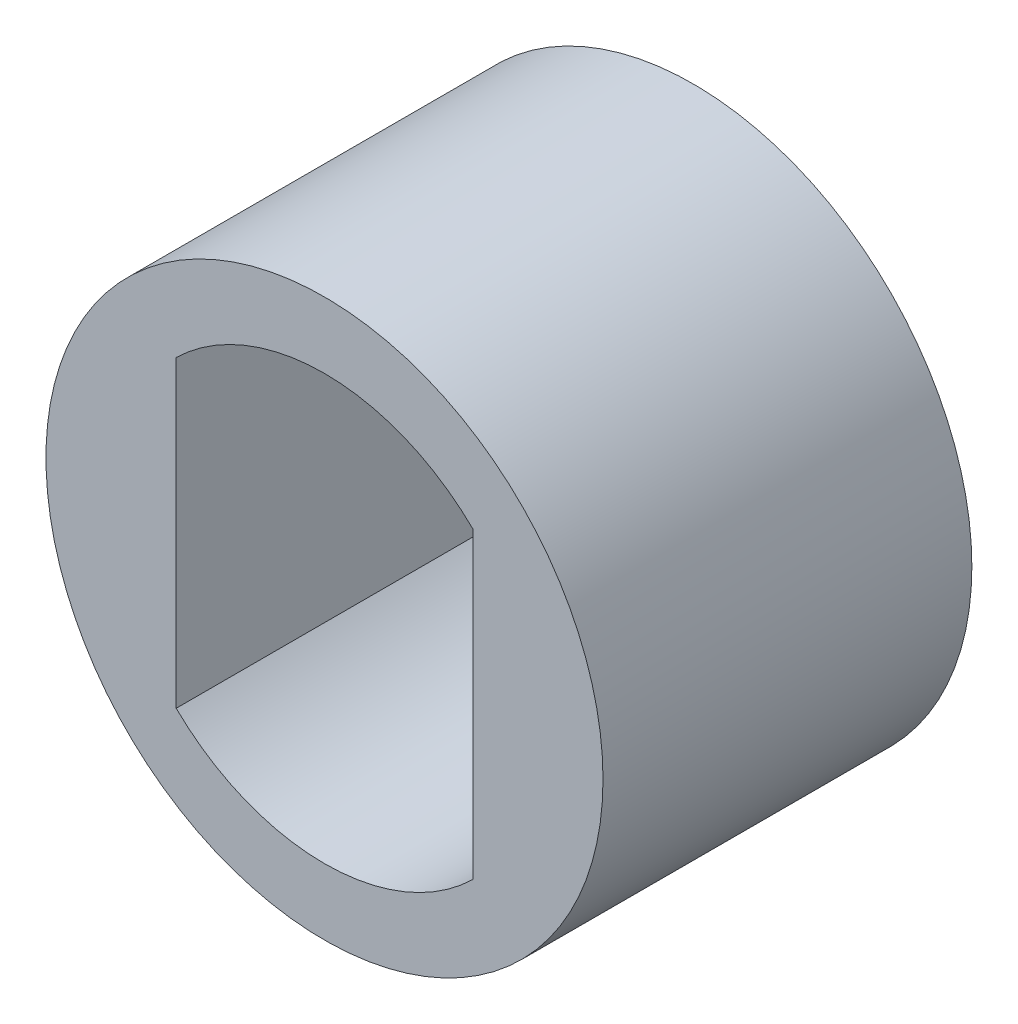
SolidWorks part; units mm, degrees
ref_plane "Plano frontal" through (0, 0, 0) normal (0, 0, 1) x (1, 0, 0)
ref_plane "Plano superior" through (0, 0, 0) normal (0, 1, 0) x (1, 0, 0)
ref_plane "Plano direito" through (0, 0, 0) normal (1, 0, 0) x (0, 0, -1)
sketch "Esboço1" plane through (0, 0, 0) normal (0, 0, 1) x (1, 0, 0)
  line L0 (2.85, -2.3596) -> (2.85, 2.3596) construction
  line L1 (-2.85, 2.3596) -> (-2.85, -2.3596) construction
  line L2 (1.85, -1.9666) -> (1.85, 1.9666) construction
  line L3 (-1.85, 1.9666) -> (-1.85, -1.9666) construction
  arc A0 (-2.85, -2.3596) -> (2.85, -2.3596) centre (0, 0) ccw construction
  arc A1 (2.85, 2.3596) -> (-2.85, 2.3596) centre (0, 0) ccw construction
  arc A2 (-1.85, -1.9666) -> (1.85, -1.9666) centre (0, 0) ccw construction
  arc A3 (1.85, 1.9666) -> (-1.85, 1.9666) centre (0, 0) ccw construction
  dimension "D1" = 3.9332
sketch "Esboço2" plane through (0, 0, 0) normal (0, 0, 1) x (1, 0, 0)
  line L6 (1.97, -2.0178) -> (1.97, 2.0178)
  line L7 (-1.97, 2.0178) -> (-1.97, -2.0178)
  line L8 (1.97, -2.0178) -> (1.97, 2.0178)
  line L9 (-1.97, 2.0178) -> (-1.97, -2.0178)
  circle A6 centre (0, 0) radius 3.7
  arc A8 (-1.97, -2.0178) -> (1.97, -2.0178) centre (0, 0) ccw
  arc A9 (1.97, 2.0178) -> (-1.97, 2.0178) centre (0, 0) ccw
  arc A10 (-1.97, -2.0178) -> (1.97, -2.0178) centre (0, 0) ccw
  arc A11 (1.97, 2.0178) -> (-1.97, 2.0178) centre (0, 0) ccw
  dimension "D1" = 0.12
extrude "Ressalto-extrusão1" add sketch "Esboço2" along normal blind 4.9
